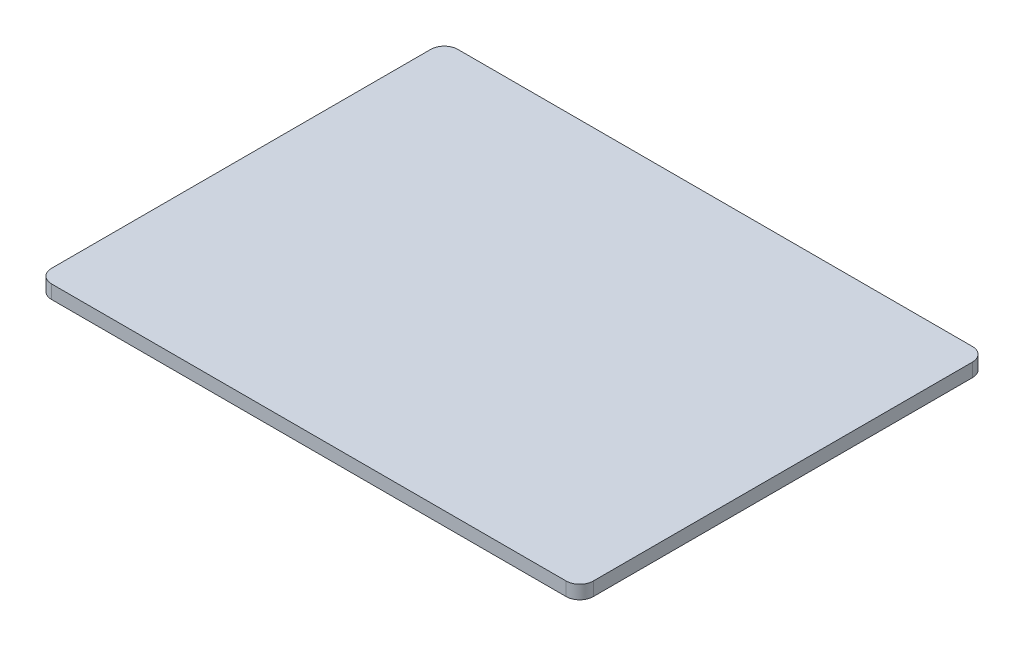
SolidWorks part; units mm, degrees
ref_plane "Front Plane" through (0, 0, 0) normal (0, 0, 1) x (1, 0, 0)
ref_plane "Top Plane" through (0, 0, 0) normal (0, 1, 0) x (1, 0, 0)
ref_plane "Right Plane" through (0, 0, 0) normal (1, 0, 0) x (0, 0, -1)
sketch "Sketch1" plane through (0, 0, 0) normal (0, 1, 0) x (1, 0, 0)
  line L1 (0, 0) -> (400, 0)
  line L2 (0, 0) -> (0, 300)
  line L3 (0, 300) -> (400, 300)
  line L4 (400, 0) -> (400, 300)
  dimension "D1" = 300
  dimension "D2" = 400
extrude "Boss-Extrude1" add sketch "Sketch1" along normal blind 10
sketch "Sketch2" plane through (0, 10, 0) normal (0, 1, 0) x (1, 0, 0)
  line L0 (400, 300) -> (0, 300) construction
  point P0 (200, 300)
fillet "Fillet1" radius 10 4 edges at (0, 5, -300) (400, 5, -300) (0, 5, 0) (400, 5, 0)
